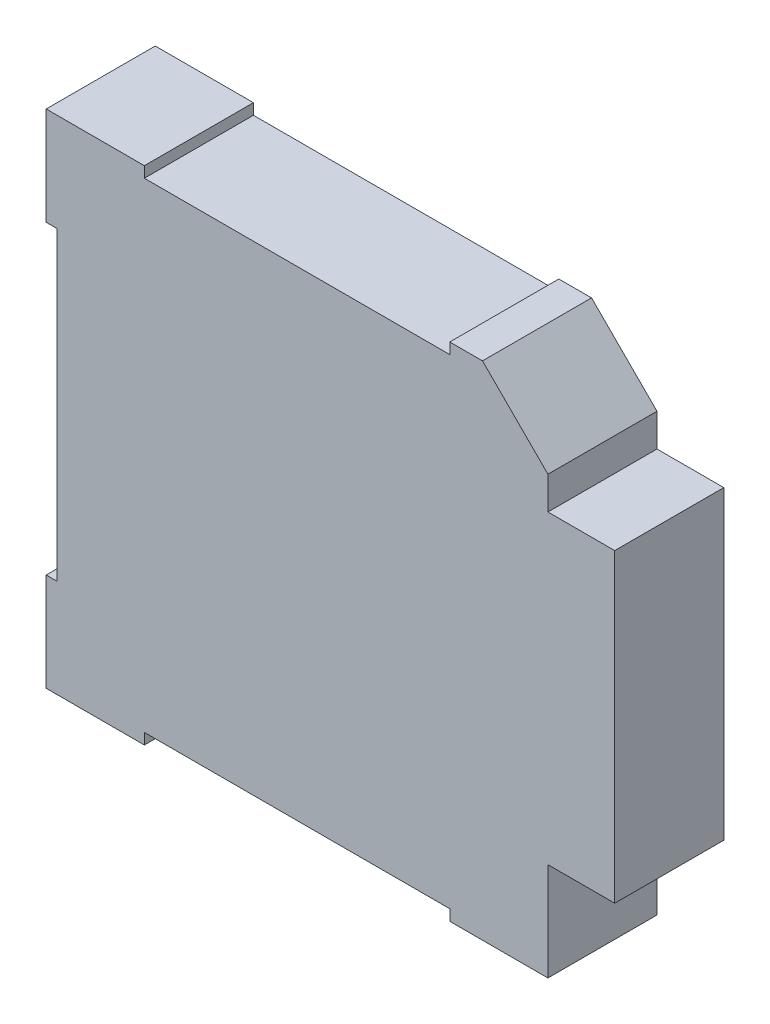
SolidWorks part; units mm, degrees
ref_plane "前视基准面" through (0, 0, 0) normal (0, 0, 1) x (1, 0, 0)
ref_plane "上视基准面" through (0, 0, 0) normal (0, 1, 0) x (1, 0, 0)
ref_plane "右视基准面" through (0, 0, 0) normal (1, 0, 0) x (0, 0, -1)
sketch "草图1" plane through (0, 0, 0) normal (0, 0, 1) x (1, 0, 0)
  line L0 (4.6, -4.6) -> (4.6, -2.8)
  line L1 (4.6, -2.8) -> (5.825, -2.8)
  line L2 (5.825, -2.8) -> (5.825, 2.8)
  line L3 (5.825, 2.8) -> (4.6, 2.8)
  line L4 (4.6, 2.8) -> (4.6, 3.4)
  line L5 (4.6, 3.4) -> (3.4, 4.6)
  line L6 (3.4, 4.6) -> (2.8, 4.6)
  line L7 (2.8, 4.6) -> (2.8, 4.4)
  line L8 (2.8, 4.4) -> (-2.8, 4.4)
  line L9 (-2.8, 4.4) -> (-2.8, 4.6)
  line L10 (-2.8, 4.6) -> (-4.6, 4.6)
  line L11 (-4.6, 4.6) -> (-4.6, 2.8)
  line L12 (-4.6, 2.8) -> (-4.4, 2.8)
  line L13 (-4.4, 2.8) -> (-4.4, -2.8)
  line L14 (-4.4, -2.8) -> (-4.6, -2.8)
  line L15 (-4.6, -2.8) -> (-4.6, -4.6)
  line L16 (-4.6, -4.6) -> (-2.8, -4.6)
  line L17 (-2.8, -4.6) -> (-2.8, -4.4)
  line L18 (-2.8, -4.4) -> (2.8, -4.4)
  line L19 (2.8, -4.4) -> (2.8, -4.6)
  line L20 (2.8, -4.6) -> (4.6, -4.6)
extrude "Component_Outline" add sketch "草图1" along normal blind 2 separate body
sketch3d "3D草图1"
  line L0 (0, 0, 0) -> (1, 0, 0)
  line L1 (0, 0, 0) -> (0, 1, 0)
  line L2 (0, 0, 0) -> (0, 0, 1)
  point P0 (0, 0, 0)
